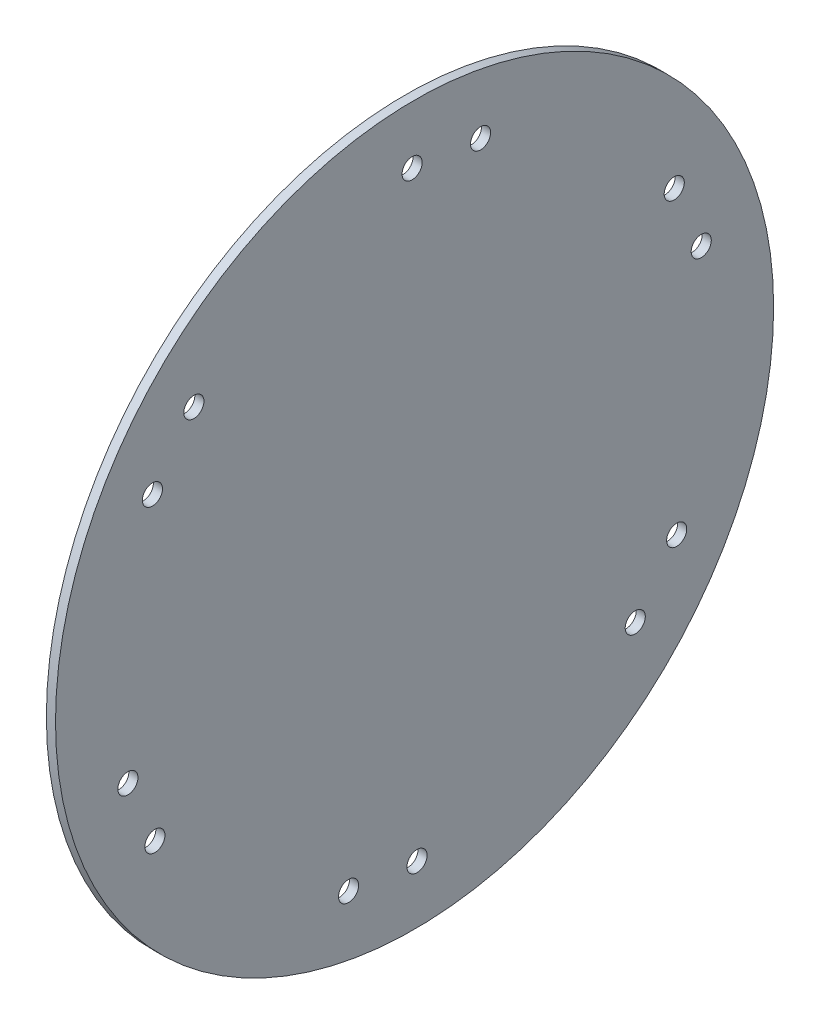
SolidWorks part; units mm, degrees
material "Oak"
ref_plane "Front Plane" through (0, 0, 0) normal (0, 0, 1) x (1, 0, 0)
ref_plane "Top Plane" through (0, 0, 0) normal (0, 1, 0) x (1, 0, 0)
ref_plane "Right Plane" through (0, 0, 0) normal (1, 0, 0) x (0, 0, -1)
sketch "Sketch2" plane through (0, 0, 0) normal (1, 0, 0) x (0, 0, -1)
  circle A0 centre (0, 0) radius 125
  dimension "D1" = 250
extrude "Boss-Extrude1" add sketch "Sketch2" along normal blind 3.18
sketch "Sketch3" plane through (0, 0, 0) normal (-1, 0, 0) x (0, 0, 1)
  circle A5 centre (22.9721, -101.9723) radius 3.5
  circle A12 centre (-0.8523, -104.8702) radius 3.5
  circle A13 centre (-91.2464, -51.697) radius 3.5
  circle A14 centre (-76.8245, -70.8806) radius 3.5
  circle A15 centre (-99.7966, 31.0917) radius 3.5
  circle A16 centre (-90.3941, 53.1732) radius 3.5
  circle A17 centre (0.8523, 104.8702) radius 3.5
  circle A18 centre (-22.9721, 101.9723) radius 3.5
  circle A19 centre (76.8245, 70.8806) radius 3.5
  circle A20 centre (91.2464, 51.697) radius 3.5
  circle A21 centre (99.7966, -31.0917) radius 3.5
  circle A22 centre (90.3941, -53.1732) radius 3.5
  dimension "D1" = 7
extrude "Cut-Extrude1" cut sketch "Sketch3" against normal through all
